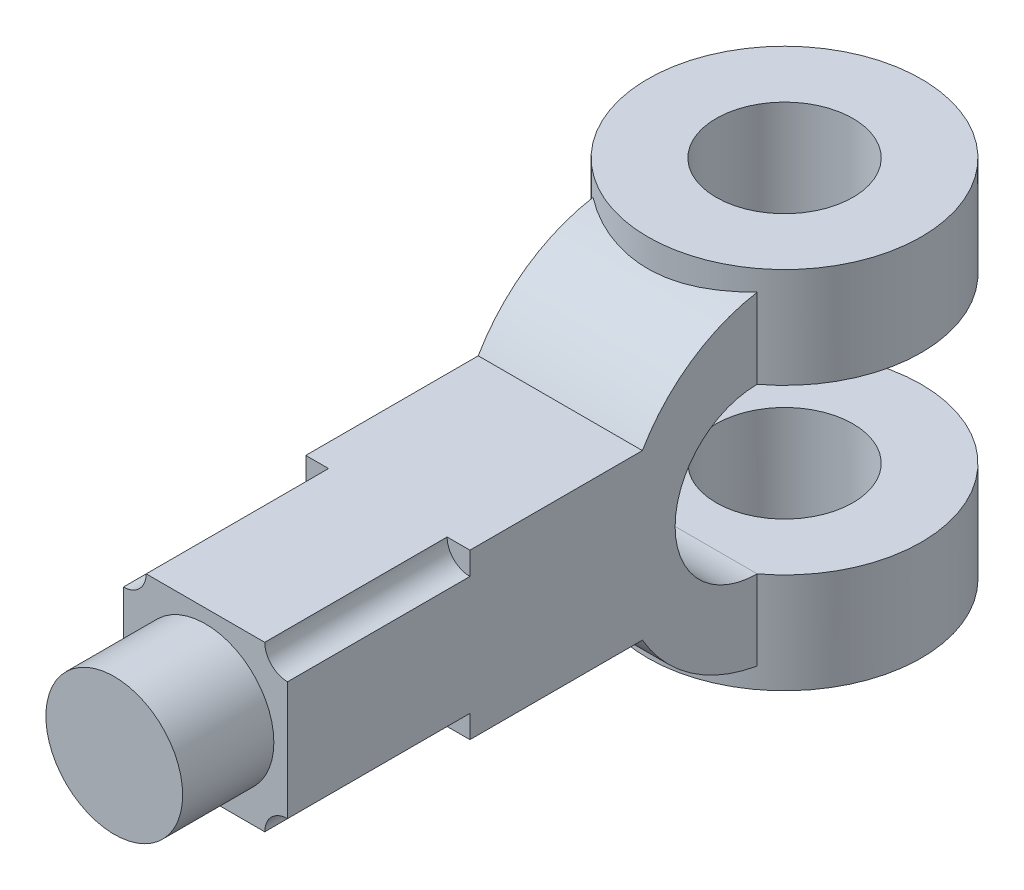
SolidWorks part; units mm, degrees
ref_plane "Front Plane" through (0, 0, 0) normal (0, 0, 1) x (1, 0, 0)
ref_plane "Top Plane" through (0, 0, 0) normal (0, 1, 0) x (1, 0, 0)
ref_plane "Right Plane" through (0, 0, 0) normal (1, 0, 0) x (0, 0, -1)
sketch "Sketch1" plane through (0, 0, 0) normal (1, 0, 0) x (0, 0, -1)
  circle A0 centre (0, 0) radius 36
  dimension "D1" = 72
extrude "Boss-Extrude1" add sketch "Sketch1" along normal mid plane 36
sketch "Sketch2" plane through (0, 0, 0) normal (0, 0, 1) x (1, 0, 0)
  line L1 (-18, 18) -> (18, 18)
  line L2 (-18, 18) -> (-18, -18)
  line L3 (-18, -18) -> (18, -18)
  line L4 (18, 18) -> (18, -18)
  line L5 (-18, 18) -> (18, -18) construction
  line L6 (-18, -18) -> (18, 18) construction
  point P0 (0, 0)
  dimension "D1" = 36
  dimension "D2" = 36
extrude "Boss-Extrude2" add sketch "Sketch2" along normal blind 109
sketch "Sketch3" plane through (0, 0, 109) normal (0, 0, 1) x (1, 0, 0)
  circle A0 centre (0, 0) radius 15
  dimension "D1" = 30
extrude "Boss-Extrude3" add sketch "Sketch3" along normal blind 20
sketch "Sketch4" plane through (0, 0, 109) normal (0, 0, 1) x (1, 0, 0)
  line L0 (18, 18) -> (-18, 18) construction
  line L1 (18, -18) -> (18, 18) construction
  line L2 (13, 18) -> (18, 18)
  line L3 (18, 18) -> (18, 13)
  arc A0 (13, 18) -> (18, 13) centre (18, 18) ccw
  dimension "D1" = 5
extrude "Cut-Extrude1" cut sketch "Sketch4" against normal blind 40
pattern_circular "CirPattern1" count 4 over 360 about axis through (0, 0, 0) along (0, 0, 1) of "Cut-Extrude1"
sketch "Sketch5" plane through (0, 0, 0) normal (0, 1, 0) x (1, 0, 0)
  line L0 (-15, -129) -> (15, -129) construction
  circle A0 centre (0, 18) radius 30
  dimension "D2" = 60
  dimension "D1" = 147
extrude "Boss-Extrude4" add sketch "Sketch5" along normal mid plane 80
sketch "Sketch6" plane through (0, 0, 0) normal (1, 0, 0) x (0, 0, -1)
  line L0 (-6, -35.4965) -> (-6, 35.4965) construction
  line L1 (-6, 18) -> (48, 18)
  line L2 (48, -40) -> (48, 40) construction
  line L3 (48, 18) -> (48, -18)
  line L4 (48, -18) -> (-6, -18)
  arc A0 (-6, 18) -> (-6, -18) centre (-6, 0) ccw
  dimension "D1" = 18
extrude "Cut-Extrude2" cut sketch "Sketch6" against normal through all both and the other way through all
hole_wizard "Hole1" positions "Sketch7" profile "Sketch8" legacy end condition through all
sketch "Sketch7" plane through (0, 40, 0) normal (0, 1, 0) x (1, 0, 0)
  point P0 (0, 18)
sketch "Sketch8" plane through (0, 40, -18) normal (1, 0, 0) x (0, 0, 1)
  line L0 (0, 0) -> (0, 80)
  line L1 (0, 80) -> (15, 80)
  line L2 (15, 80) -> (15, 0)
  line L3 (15, 0) -> (0, 0)
  line L4 (0, 110) -> (0, -10) construction
  dimension "Diameter" = 30
  dimension "Depth" = 80
